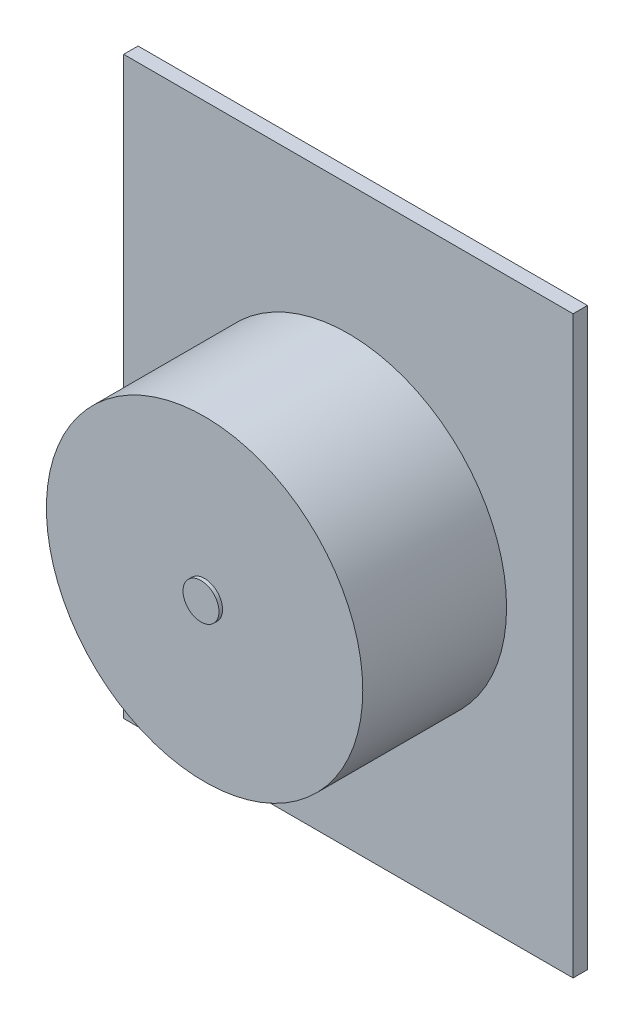
SolidWorks part; units mm, degrees
ref_plane "Plan de face" through (0, 0, 0) normal (0, 0, 1) x (1, 0, 0)
ref_plane "Plan de dessus" through (0, 0, 0) normal (0, 1, 0) x (1, 0, 0)
ref_plane "Plan de droite" through (0, 0, 0) normal (1, 0, 0) x (0, 0, -1)
sketch "Esquisse1" plane through (0, 0, 0) normal (0, 0, 1) x (1, 0, 0)
  line L1 (0, 0) -> (-1250, 0)
  line L2 (0, 0) -> (0, 1600)
  line L3 (0, 1600) -> (-1250, 1600)
  line L4 (-1250, 0) -> (-1250, 1600)
  dimension "D1" = 1250
  dimension "D2" = 1600
extrude "Boss.-Extru.1" add sketch "Esquisse1" along normal blind 40
sketch "Esquisse2" plane through (0, 0, 40) normal (0, 0, 1) x (1, 0, 0)
  circle A0 centre (-625, 800) radius 440
  point P0 (-625, 800)
  dimension "D1" = 880
extrude "Boss.-Extru.2" add sketch "Esquisse2" along normal blind 400
sketch "Esquisse3" plane through (0, 0, 440) normal (0, 0, 1) x (1, 0, 0)
  circle A0 centre (-625, 800) radius 50
  circle A2 centre (-625, 800) radius 440 construction
  dimension "D1" = 100
extrude "Boss.-Extru.3" add sketch "Esquisse3" along normal blind 10
